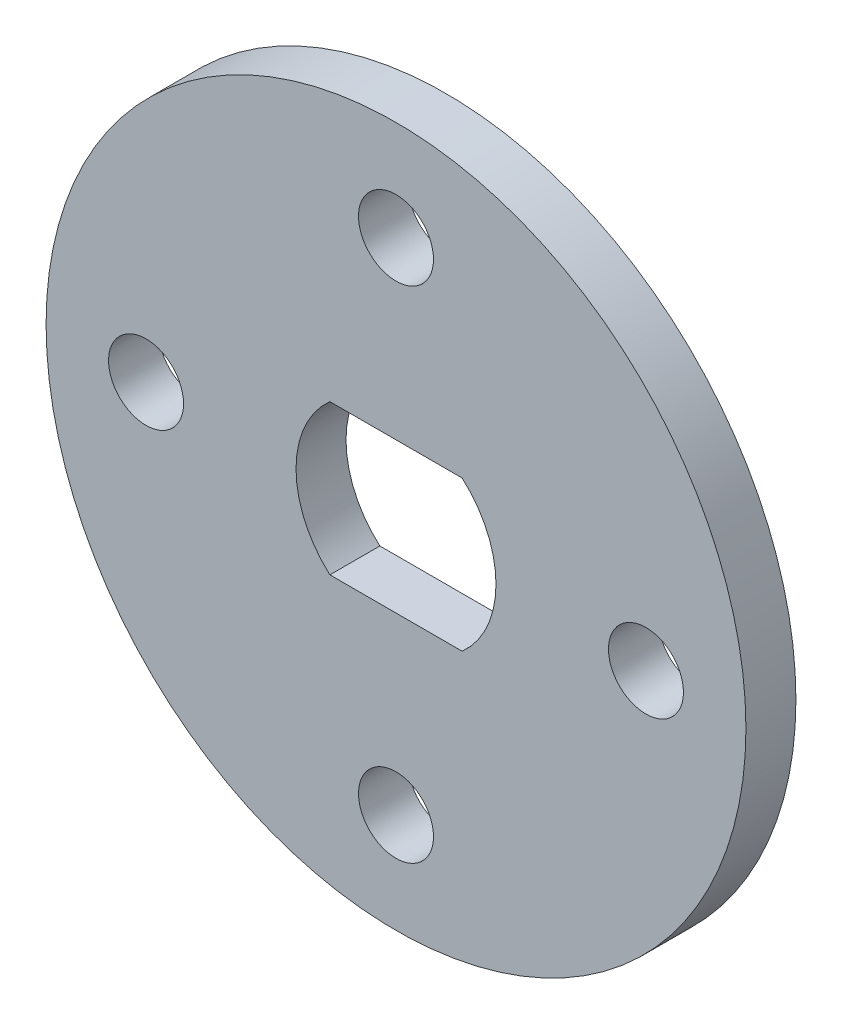
SolidWorks part; units mm, degrees
ref_plane "前视基准面" through (0, 0, 0) normal (0, 0, 1) x (1, 0, 0)
ref_plane "上视基准面" through (0, 0, 0) normal (0, 1, 0) x (1, 0, 0)
ref_plane "右视基准面" through (0, 0, 0) normal (1, 0, 0) x (0, 0, -1)
sketch "草图1" plane through (0, 0, 0) normal (0, 0, 1) x (1, 0, 0)
  circle A1 centre (0, 0) radius 14
  circle A3 centre (0, 10) radius 1.5
  circle A4 centre (10, 0) radius 1.5
  circle A5 centre (-10, 0) radius 1.5
  circle A6 centre (0, -10) radius 1.5
extrude "凸台-拉伸1" add sketch "草图1" along normal blind 2
sketch "草图2" plane through (0, 0, 0) normal (0, 0, -1) x (-1, 0, 0)
  line L9 (-2.6885, -3) -> (2.6885, -3)
  line L10 (-2.6458, 3) -> (2.6458, 3)
  line L14 (-2.6458, -3) -> (2.6458, -3)
  arc A1 (-2.6458, 3) -> (-2.6458, -3) centre (0, 0) ccw
  arc A2 (2.6458, 3) -> (2.6458, -3) centre (0, 0) cw
extrude "切除-拉伸1" cut sketch "草图2" against normal through all contours A2 L10 A1 L9
